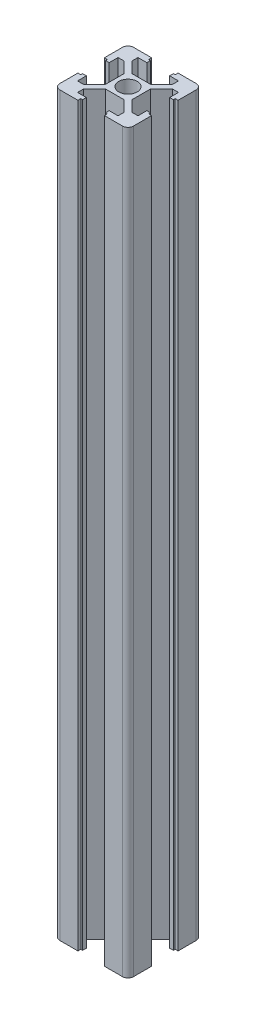
SolidWorks part; units mm, degrees
ref_plane "前视基准面" through (0, 0, 0) normal (0, 0, 1) x (1, 0, 0)
ref_plane "上视基准面" through (0, 0, 0) normal (0, 1, 0) x (1, 0, 0)
ref_plane "右视基准面" through (0, 0, 0) normal (1, 0, 0) x (0, 0, -1)
other "Configuration Table"
sketch "草图1" plane through (0, 0, 0) normal (0, 1, 0) x (1, 0, 0)
  line L0 (-4.4156, 1.3346) -> (-4.4156, 4.4346) construction
  line L1 (-4.4156, 3.874) -> (-4.4156, -1.2047)
  line L2 (1.7237, 4.9346) -> (-3.3549, 4.9346)
  line L3 (2.7844, -1.2047) -> (2.7844, 3.874)
  line L4 (-3.3549, -2.2654) -> (1.7237, -2.2654)
  line L5 (-10.8156, 1.3346) -> (9.1844, 1.3346) construction
  line L6 (-0.8156, 11.3346) -> (-0.8156, -8.6654) construction
  line L7 (-10.8156, 11.3346) -> (-0.8156, 1.3346) construction
  line L8 (-10.8156, 4.9346) -> (-4.4156, 4.9346) construction
  line L9 (-10.0156, 4.4346) -> (-3.9156, 4.4346) construction
  line L10 (-9.0156, 6.8346) -> (-6.3156, 6.8346) construction
  line L11 (-7.3763, 6.8346) -> (-4.4156, 3.874) construction
  line L12 (-10.8156, 9.8346) -> (-10.8156, 4.9346)
  line L13 (-10.8156, 4.9346) -> (-10.0156, 4.9346)
  line L14 (-10.0156, 4.9346) -> (-10.0156, 4.4346)
  line L15 (-10.0156, 4.4346) -> (-9.0156, 4.4346)
  line L16 (-9.0156, 4.4346) -> (-9.0156, 6.8346)
  line L17 (-9.0156, 6.8346) -> (-7.3763, 6.8346)
  line L18 (-7.3763, 6.8346) -> (-4.4156, 3.874)
  line L19 (-3.9156, 10.5346) -> (-3.9156, 9.5346)
  line L20 (-4.4156, 10.5346) -> (-3.9156, 10.5346)
  line L21 (-4.4156, 11.3346) -> (-4.4156, 10.5346)
  line L22 (-9.3156, 11.3346) -> (-4.4156, 11.3346)
  line L23 (-3.9156, 9.5346) -> (-6.3156, 9.5346)
  line L24 (-6.3156, 9.5346) -> (-6.3156, 7.8953)
  line L25 (-6.3156, 7.8953) -> (-3.3549, 4.9346)
  line L26 (9.1844, 11.3346) -> (-0.8156, 1.3346) construction
  line L27 (4.6844, 7.8953) -> (1.7237, 4.9346)
  line L28 (4.6844, 9.5346) -> (4.6844, 7.8953)
  line L29 (2.2844, 9.5346) -> (4.6844, 9.5346)
  line L30 (2.2844, 10.5346) -> (2.2844, 9.5346)
  line L31 (2.7844, 10.5346) -> (2.2844, 10.5346)
  line L32 (2.7844, 11.3346) -> (2.7844, 10.5346)
  line L33 (7.6844, 11.3346) -> (2.7844, 11.3346)
  line L34 (9.1844, 9.8346) -> (9.1844, 4.9346)
  line L35 (9.1844, 4.9346) -> (8.3844, 4.9346)
  line L36 (8.3844, 4.9346) -> (8.3844, 4.4346)
  line L37 (8.3844, 4.4346) -> (7.3844, 4.4346)
  line L38 (7.3844, 4.4346) -> (7.3844, 6.8346)
  line L39 (7.3844, 6.8346) -> (5.7451, 6.8346)
  line L40 (5.7451, 6.8346) -> (2.7844, 3.874)
  line L41 (9.1844, -8.6654) -> (-0.8156, 1.3346) construction
  line L42 (5.7451, -4.1654) -> (2.7844, -1.2047)
  line L43 (7.3844, -4.1654) -> (5.7451, -4.1654)
  line L44 (7.3844, -1.7654) -> (7.3844, -4.1654)
  line L45 (8.3844, -1.7654) -> (7.3844, -1.7654)
  line L46 (8.3844, -2.2654) -> (8.3844, -1.7654)
  line L47 (9.1844, -2.2654) -> (8.3844, -2.2654)
  line L48 (9.1844, -7.1654) -> (9.1844, -2.2654)
  line L49 (7.6844, -8.6654) -> (2.7844, -8.6654)
  line L50 (2.7844, -8.6654) -> (2.7844, -7.8654)
  line L51 (2.7844, -7.8654) -> (2.2844, -7.8654)
  line L52 (2.2844, -7.8654) -> (2.2844, -6.8654)
  line L53 (2.2844, -6.8654) -> (4.6844, -6.8654)
  line L54 (4.6844, -6.8654) -> (4.6844, -5.226)
  line L55 (4.6844, -5.226) -> (1.7237, -2.2654)
  line L56 (-10.8156, -8.6654) -> (-0.8156, 1.3346) construction
  line L57 (-6.3156, -5.226) -> (-3.3549, -2.2654)
  line L58 (-6.3156, -6.8654) -> (-6.3156, -5.226)
  line L59 (-3.9156, -6.8654) -> (-6.3156, -6.8654)
  line L60 (-3.9156, -7.8654) -> (-3.9156, -6.8654)
  line L61 (-4.4156, -7.8654) -> (-3.9156, -7.8654)
  line L62 (-4.4156, -8.6654) -> (-4.4156, -7.8654)
  line L63 (-9.3156, -8.6654) -> (-4.4156, -8.6654)
  line L64 (-10.8156, -7.1654) -> (-10.8156, -2.2654)
  line L65 (-10.8156, -2.2654) -> (-10.0156, -2.2654)
  line L66 (-10.0156, -2.2654) -> (-10.0156, -1.7654)
  line L67 (-10.0156, -1.7654) -> (-9.0156, -1.7654)
  line L68 (-9.0156, -1.7654) -> (-9.0156, -4.1654)
  line L69 (-9.0156, -4.1654) -> (-7.3763, -4.1654)
  line L70 (-7.3763, -4.1654) -> (-4.4156, -1.2047)
  arc A0 (-10.8156, 9.8346) -> (-9.3156, 11.3346) centre (-9.3156, 9.8346) cw
  circle A1 centre (-0.8156, 1.3346) radius 2.5
  arc A2 (7.6844, 11.3346) -> (9.1844, 9.8346) centre (7.6844, 9.8346) cw
  arc A3 (9.1844, -7.1654) -> (7.6844, -8.6654) centre (7.6844, -7.1654) cw
  arc A4 (-9.3156, -8.6654) -> (-10.8156, -7.1654) centre (-9.3156, -7.1654) cw
  point P13 (-0.8156, 1.3346)
  point P84 (-0.8156, 1.3346)
  dimension "D8" = 1.5
  dimension "D9" = 5
  dimension "D1" = 20
  dimension "D2" = 6.2
  dimension "D3" = 7.2
  dimension "D4" = 11
  dimension "D5" = 1.5
  dimension "D6" = 0.8
  dimension "D7" = 1.8
  dimension "D10" = 7.2
extrude "凸台-拉伸1" add sketch "草图1" along normal blind 200
